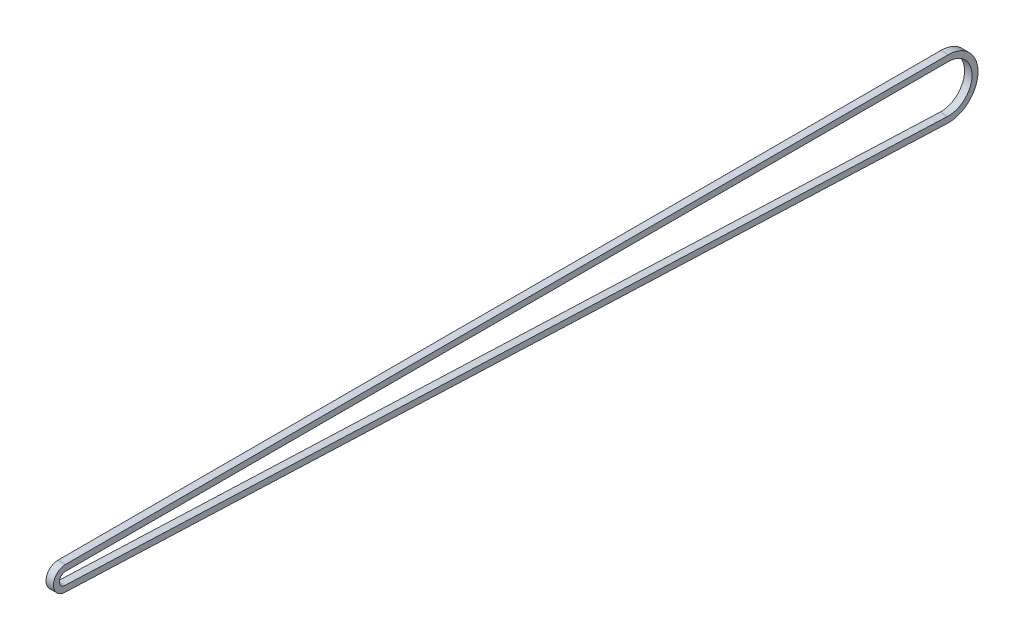
SolidWorks part; units mm, degrees
material "ｺﾞﾑ"
ref_plane "正面" through (0, 0, 0) normal (0, 0, 1) x (1, 0, 0)
ref_plane "平面" through (0, 0, 0) normal (0, 1, 0) x (1, 0, 0)
ref_plane "右側面" through (0, 0, 0) normal (1, 0, 0) x (0, 0, -1)
sketch "ｽｹｯﾁ1" plane through (0, 0, 0) normal (1, 0, 0) x (0, 0, -1)
  line L0 (0, 0) -> (590.52, -11.75) construction
  line L1 (0, 8) -> (590.52, 8)
  line L2 (-0.3182, -7.9937) -> (589.7344, -31.4844)
  line L3 (0, 4) -> (590.52, 4)
  line L4 (589.8935, -27.4875) -> (-0.1591, -3.9968)
  arc A0 (0, 8) -> (-0.3182, -7.9937) centre (0, 0) ccw
  arc A1 (589.7344, -31.4844) -> (590.52, 8) centre (590.52, -11.75) ccw
  arc A2 (7.9984, -0.1592) -> (0, 8) centre (0, 0) ccw construction
  arc A3 (-0.3182, -7.9937) -> (7.9984, -0.1592) centre (0, 0) ccw construction
  arc A4 (570.7739, -11.3571) -> (589.7344, -31.4844) centre (590.52, -11.75) ccw construction
  arc A5 (590.52, 8) -> (570.7739, -11.3571) centre (590.52, -11.75) ccw construction
  circle A6 centre (590.52, -11.75) radius 15.75
  circle A7 centre (0, 0) radius 4
  dimension "D1" = 16
  dimension "D2" = 39.5
  dimension "D4" = 31.5
  dimension "D3" = 590.52
extrude "ﾎﾞｽ - 押し出し1" add sketch "ｽｹｯﾁ1" along normal blind 5 contours L2 A1 L1 A0 A7 L3 A6 L4
